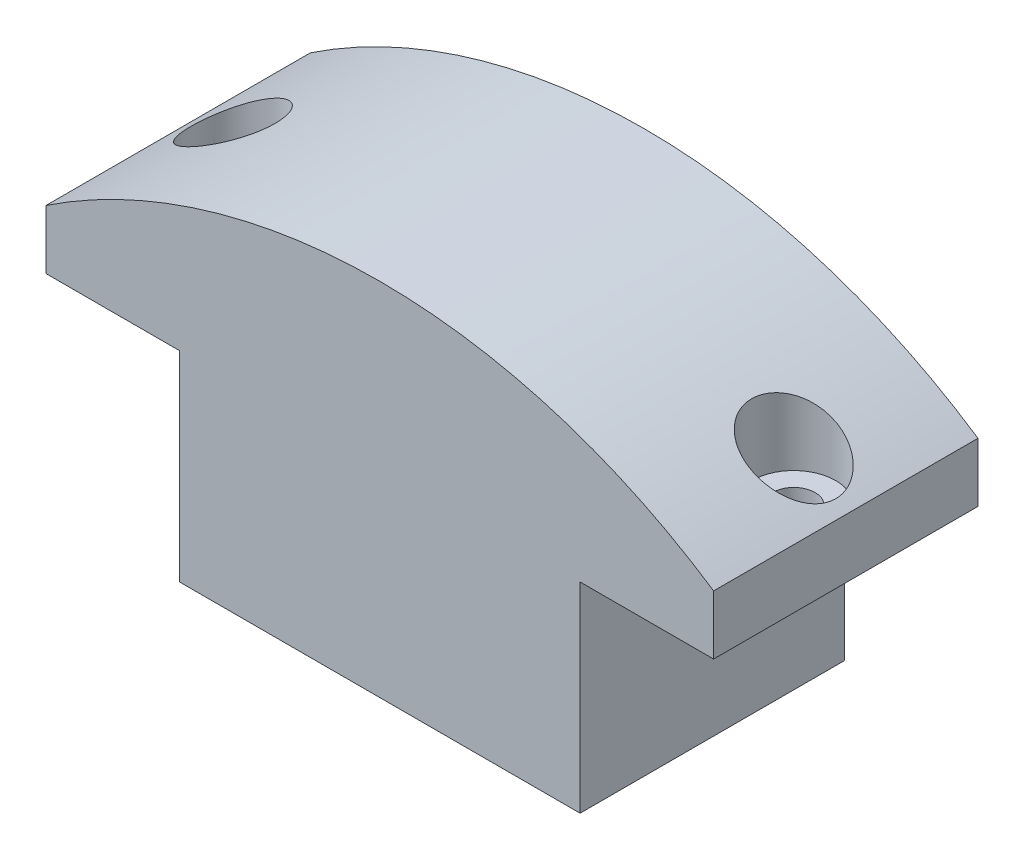
SolidWorks part; units mm, degrees
ref_plane "Plano frontal" through (0, 0, 0) normal (0, 0, 1) x (1, 0, 0)
ref_plane "Plano superior" through (0, 0, 0) normal (0, 1, 0) x (1, 0, 0)
ref_plane "Plano direito" through (0, 0, 0) normal (1, 0, 0) x (0, 0, -1)
sketch "Esboço1" plane through (0, 0, 0) normal (0, 0, 1) x (1, 0, 0)
  line L1 (-25, 37.4166) -> (-25, 32.9966)
  line L2 (-25, 32.9966) -> (-15, 32.9966)
  line L3 (25, 32.9966) -> (25, 37.4166)
  line L4 (15, 32.9966) -> (15, 17.9966)
  line L5 (15, 17.9966) -> (-15, 17.9966)
  line L6 (-15, 17.9966) -> (-15, 32.9966)
  line L7 (15, 32.9966) -> (25, 32.9966)
  arc A0 (25, 37.4166) -> (-25, 37.4166) centre (0, 0) ccw
  dimension "D1" = 90
  dimension "D2" = 50
  dimension "D3" = 4.42
  dimension "D4" = 50.195
  dimension "D5" = 30
  dimension "D6" = 15
  dimension "D7" = 10
extrude "Ressalto-extrusão1" add sketch "Esboço1" along normal blind 19.8
sketch "Esboço2" plane through (0, 32.9966, 0) normal (0, -1, 0) x (1, 0, 0)
sketch "Esboço3" plane through (0, 32.9966, 0) normal (0, -1, 0) x (1, 0, 0)
  line L0 (15, 19.8) -> (25, 19.8) construction
  line L1 (-25, 19.8) -> (-15, 19.8) construction
  line L2 (-15, 19.8) -> (-15, 0) construction
  line L3 (15, 19.8) -> (15, 0) construction
  circle A0 centre (21, 9.8) radius 1.6
  circle A1 centre (-21, 9.8) radius 1.6
  dimension "D1" = 3.2
  dimension "D2" = 3.2
  dimension "D4" = 10
  dimension "D5" = 6
  dimension "D6" = 6
  dimension "D3" = 10
extrude "Corte-extrusão1" cut sketch "Esboço3" against normal blind 3
sketch "Esboço4" plane through (0, 35.9966, 0) normal (0, -1, 0) x (1, 0, 0)
  circle A0 centre (21, 9.8) radius 3.15
  circle A1 centre (-21, 9.8) radius 3.15
  dimension "D1" = 6.3
  dimension "D2" = 6.3
extrude "Corte-extrusão2" cut sketch "Esboço4" against normal up to surface (3.8029 mm away)
